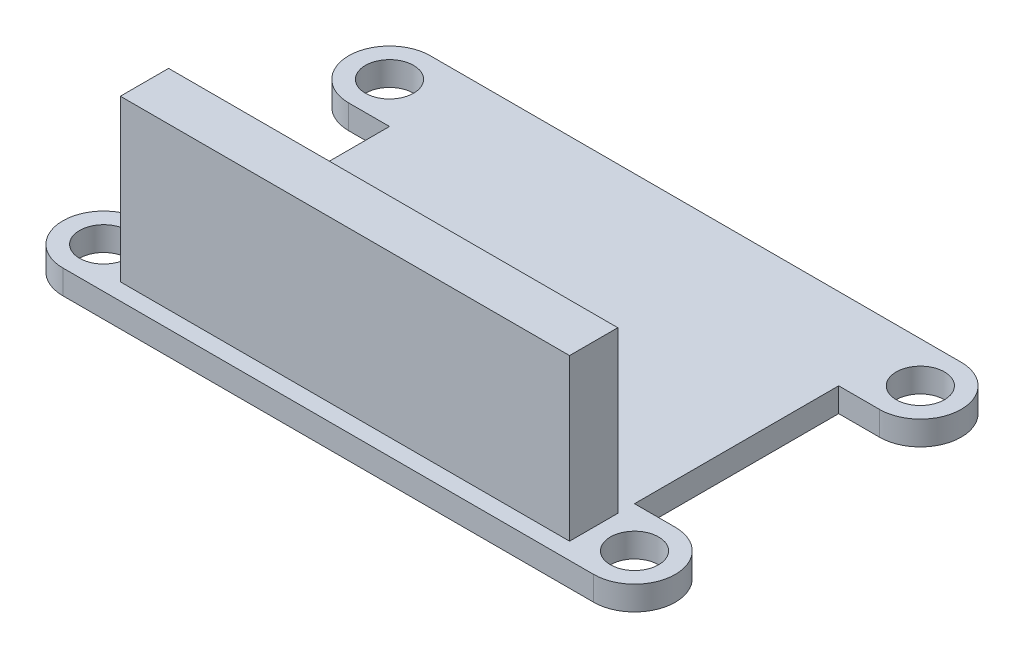
SolidWorks part; units mm, degrees
ref_plane "Спереди" through (0, 0, 0) normal (0, 0, 1) x (1, 0, 0)
ref_plane "Сверху" through (0, 0, 0) normal (0, 1, 0) x (1, 0, 0)
ref_plane "Справа" through (0, 0, 0) normal (1, 0, 0) x (0, 0, -1)
sketch "Эскиз1" plane through (0, 0, 0) normal (0, 1, 0) x (1, 0, 0)
  line L0 (2.54, 0) -> (35.56, 0)
  line L2 (35.56, 22.86) -> (2.54, 22.86)
  line L3 (19.05, 22.86) -> (19.05, -4.4464) construction
  line L4 (19.05, 22.86) -> (2.54, 22.86)
  line L5 (2.54, 22.86) -> (2.54, 0) construction
  line L6 (2.54, 11.43) -> (2.54, 20.32) construction
  line L7 (2.54, 11.43) -> (2.54, 2.54) construction
  line L8 (5.08, 17.78) -> (5.08, 5.08)
  line L9 (2.54, 17.78) -> (5.08, 17.78)
  line L10 (2.54, 5.08) -> (5.08, 5.08)
  line L11 (35.56, 11.43) -> (35.56, 2.54) construction
  line L12 (35.56, 11.43) -> (35.56, 20.32) construction
  line L13 (35.56, 22.86) -> (35.56, 0) construction
  line L14 (35.56, 5.08) -> (33.02, 5.08)
  line L15 (35.56, 17.78) -> (33.02, 17.78)
  line L16 (33.02, 17.78) -> (33.02, 5.08)
  circle A0 centre (2.54, 20.32) radius 1.5
  circle A1 centre (2.54, 2.54) radius 1.5
  arc A2 (2.54, 22.86) -> (2.54, 17.78) centre (2.54, 20.32) ccw
  arc A3 (2.54, 5.08) -> (2.54, 0) centre (2.54, 2.54) ccw
  arc A4 (35.56, 5.08) -> (35.56, 0) centre (35.56, 2.54) cw
  arc A5 (35.56, 22.86) -> (35.56, 17.78) centre (35.56, 20.32) cw
  circle A6 centre (35.56, 2.54) radius 1.5
  circle A7 centre (35.56, 20.32) radius 1.5
extrude "Бобышка-Вытянуть1" add sketch "Эскиз1" along normal blind 1.5 contours A5 L2 A2 L9 L8 L10 A3 L0 A4 L14 L16 L15 A6 A1 A0 A7
sketch "Эскиз2" plane through (0, 1.5, 0) normal (0, 1, 0) x (1, 0, 0)
  line L0 (33.02, 4.04) -> (33.02, 1.04)
  line L4 (33.02, 5.08) -> (33.02, 4.04)
  line L5 (5.08, 4.04) -> (33.02, 4.04)
  line L6 (5.08, 4.04) -> (5.08, 1.04)
  line L7 (33.02, 1.04) -> (5.08, 1.04)
  line L8 (5.08, 1.04) -> (5.08, 4.04)
extrude "Бобышка-Вытянуть2" add sketch "Эскиз2" along normal blind 10 contours L7 L0 L5 L6
ref_plane "Плоскость1" through (0, 0, -11.43) normal (0, 0, 1) x (1, 0, 0)
